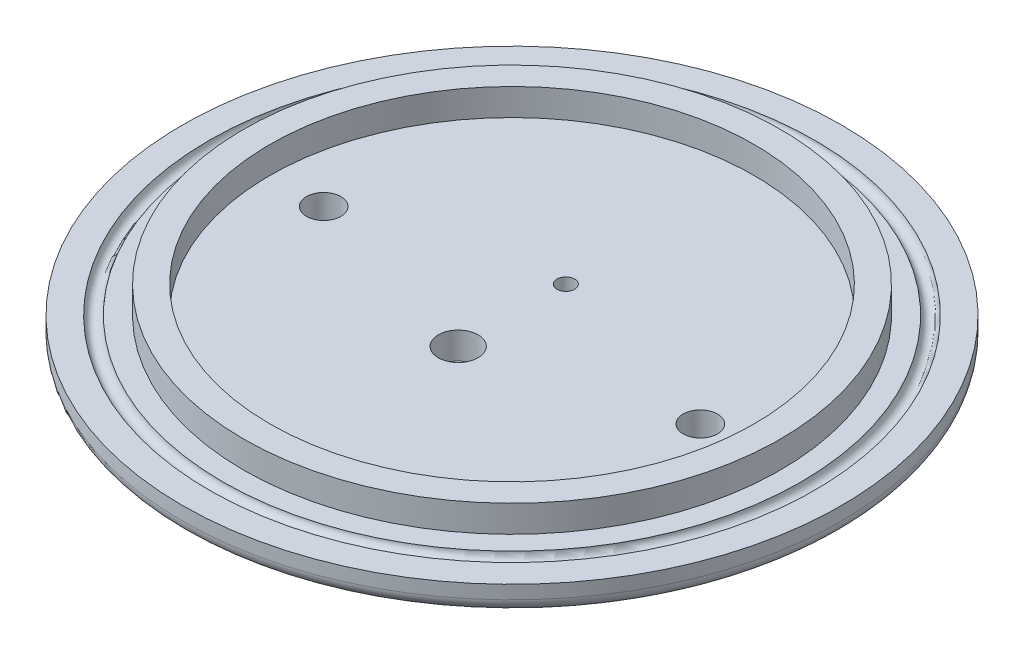
SolidWorks part; units mm, degrees
ref_plane "Alzado" through (0, 0, 0) normal (0, 0, 1) x (1, 0, 0)
ref_plane "Planta" through (0, 0, 0) normal (0, 1, 0) x (1, 0, 0)
ref_plane "Vista lateral" through (0, 0, 0) normal (1, 0, 0) x (0, 0, -1)
sketch "Croquis1" plane through (0, 0, 0) normal (0, 1, 0) x (1, 0, 0)
  circle A0 centre (0, 0) radius 122.5
  dimension "D1" = 245
extrude "Saliente-Extruir1" add sketch "Croquis1" along normal blind 10
sketch "Croquis2" plane through (0, 10, 0) normal (0, 1, 0) x (1, 0, 0)
  circle A0 centre (0, 0) radius 120.2
  circle A1 centre (0, 0) radius 125
  dimension "D1" = 240.4
  dimension "D2" = 250
extrude "Saliente-Extruir2" [suppressed] add sketch "Croquis2" along normal blind 10
sketch "Croquis3" plane through (0, 10, 0) normal (0, 1, 0) x (1, 0, 0)
  circle A0 centre (0, 0) radius 110
  dimension "D1" = 220
sketch "Croquis4" plane through (0, 0, 0) normal (0, 0, 1) x (1, 0, 0)
  line L0 (110, 10) -> (-110, 10) construction
  line L1 (110, 10) -> (-110, 10) construction
  circle A0 centre (-110, 10) radius 2.6
  dimension "D1" = 5.2
sweep "Cortar-Barrer1" cut profiles "Croquis4" path "Croquis3"
sketch "Croquis5" plane through (0, 10, 0) normal (0, 1, 0) x (1, 0, 0)
  circle A0 centre (0, 0) radius 99.75
  circle A1 centre (0, 0) radius 90
  dimension "D1" = 199.5
  dimension "D2" = 180
extrude "Saliente-Extruir3" add sketch "Croquis5" along normal blind 10
ref_plane "Plano1" through (90, 0, 0) normal (1, 0, 0) x (0, 0, -1)
sketch "Croquis6" plane through (90, 0, 0) normal (1, 0, 0) x (0, 0, -1)
  line L0 (0, 0) -> (0, 13) construction
  line L1 (0, 13) -> (0, 21)
  line L2 (0, 21) -> (3, 21)
  line L3 (3, 21) -> (3, 16)
  line L4 (3, 16) -> (12, 16)
  line L5 (12, 16) -> (12, 13)
  line L6 (12, 13) -> (0, 13)
  dimension "D1" = 13
  dimension "D2" = 8
  dimension "D3" = 12
  dimension "D4" = 3
  dimension "D5" = 3
extrude "Saliente-Extruir4" [suppressed] add sketch "Croquis6" along normal blind 10
fillet "Redondeo1" radius 5 1 edges at (0, 0, 122.5)
sketch "Croquis7" plane through (0, 0, 0) normal (0, -1, 0) x (1, 0, 0)
  line L0 (0, 0) -> (0, 20) construction
  line L1 (0, 0) -> (0, -20) construction
  line L2 (0, 0) -> (70, 0) construction
  line L3 (0, 0) -> (-70, 0) construction
  line L5 (-75.5, 2.9) -> (-64.5, 2.9)
  line L6 (-75.5, 2.9) -> (-75.5, -2.9)
  line L7 (-75.5, -2.9) -> (-64.5, -2.9)
  line L8 (-64.5, 2.9) -> (-64.5, -2.9)
  line L9 (-75.5, 2.9) -> (-64.5, -2.9) construction
  line L10 (-75.5, -2.9) -> (-64.5, 2.9) construction
  circle A0 centre (0, 20) radius 7.4
  circle A1 centre (0, -20) radius 3.3
  circle A3 centre (70, 0) radius 6.4
  circle A4 centre (-70, 0) radius 6.4
  dimension "D1" = 6.6
  dimension "D2" = 14.8
  dimension "D3" = 20
  dimension "D7" = 12.8
  dimension "D8" = 12.8
  dimension "D4" = 20
  dimension "D5" = 70
  dimension "D6" = 70
  dimension "D9" = 11
  dimension "D10" = 5.8
extrude "Cortar-Extruir1" cut sketch "Croquis7" against normal through all contours A4 | A0 | A1 | A3
